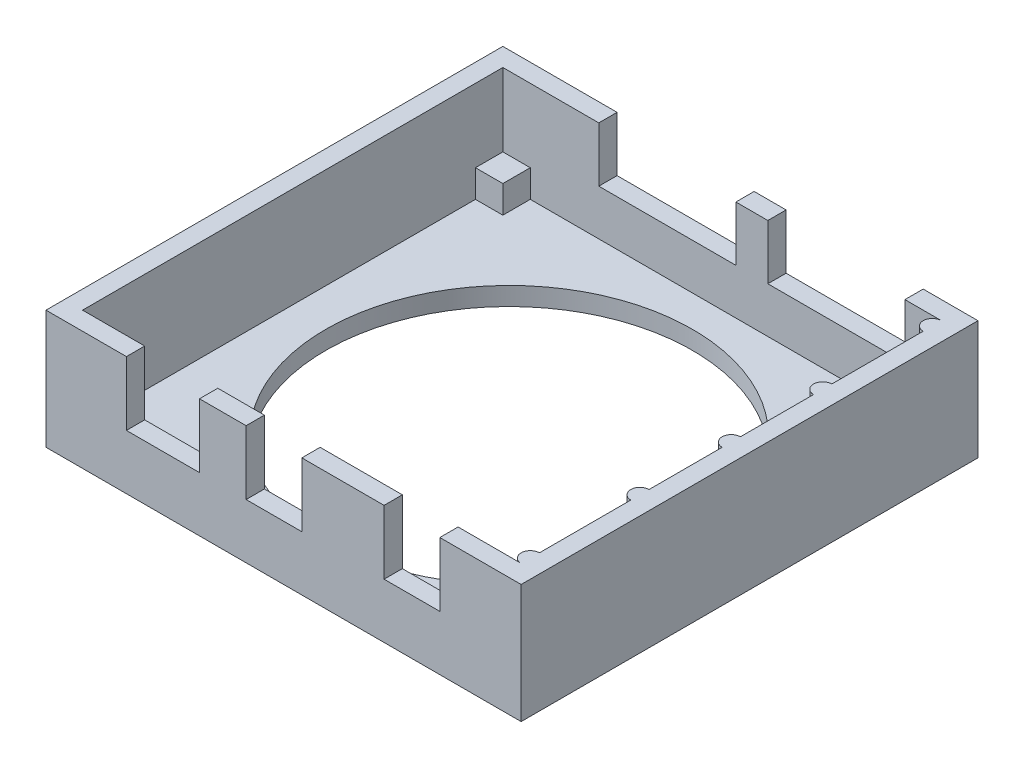
SolidWorks part; units mm, degrees
ref_plane "Front Plane" through (0, 0, 0) normal (0, 0, 1) x (1, 0, 0)
ref_plane "Top Plane" through (0, 0, 0) normal (0, 1, 0) x (1, 0, 0)
ref_plane "Right Plane" through (0, 0, 0) normal (1, 0, 0) x (0, 0, -1)
sketch "Sketch1" plane through (0, 0, 0) normal (0, 1, 0) x (1, 0, 0)
  line L1 (0, 50) -> (52, 50)
  line L2 (0, 50) -> (0, 0)
  line L3 (0, 0) -> (52, 0)
  line L4 (52, 50) -> (52, 0)
  dimension "D1" = 52
  dimension "D2" = 50
extrude "Boss-Extrude1" add sketch "Sketch1" along normal blind 13
sketch "Sketch2" plane through (0, 13, 0) normal (0, 1, 0) x (1, 0, 0)
  line L0 (0, 25) -> (52, 25) construction
  line L1 (2, 2) -> (50, 2)
  line L2 (2, 2) -> (2, 48)
  line L3 (2, 48) -> (50, 48)
  line L4 (50, 2) -> (50, 48)
  line L5 (0, 50) -> (0, 0) construction
  line L6 (52, 0) -> (52, 50) construction
  line L7 (26, 0) -> (26, 50) construction
  line L8 (0, 0) -> (52, 0) construction
  line L9 (52, 50) -> (0, 50) construction
  point P10 (2, 25)
  point P11 (26, 2)
  dimension "D1" = 46
  dimension "D2" = 48
extrude "Cut-Extrude1" cut sketch "Sketch2" against normal blind 11
sketch "Sketch3" plane through (0, 13, 0) normal (0, 1, 0) x (1, 0, 0)
  line L6 (50, 2) -> (50, 48) construction
  line L11 (2, 2) -> (50, 2) construction
  line L12 (43.1, 2) -> (37, 2)
  line L13 (43.1, 2) -> (43.1, 0)
  line L14 (43.1, 0) -> (37, 0)
  line L15 (37, 2) -> (37, 0)
  line L16 (0, 0) -> (52, 0) construction
  line L18 (28, 2) -> (21.9, 2)
  line L19 (28, 2) -> (28, 0)
  line L20 (28, 0) -> (21.9, 0)
  line L21 (21.9, 2) -> (21.9, 0)
  line L22 (16.8, 2) -> (8.8, 2)
  line L23 (16.8, 2) -> (16.8, 0)
  line L24 (16.8, 0) -> (8.8, 0)
  line L25 (8.8, 2) -> (8.8, 0)
  dimension "D5" = 6.9
  dimension "D6" = 6.1
  dimension "D7" = 9
  dimension "D8" = 6.1
  dimension "D9" = 5.1
  dimension "D10" = 8
extrude "Cut-Extrude2" cut sketch "Sketch3" against normal blind 7
sketch "Sketch4" plane through (0, 2, 0) normal (0, 1, 0) x (1, 0, 0)
  line L0 (2, 2) -> (50, 2) construction
  line L1 (2, 48) -> (5, 48)
  line L2 (2, 48) -> (2, 45)
  line L3 (2, 45) -> (5, 45)
  line L4 (5, 48) -> (5, 45)
  line L5 (50, 48) -> (47, 48)
  line L6 (50, 48) -> (50, 45)
  line L7 (50, 45) -> (47, 45)
  line L8 (47, 48) -> (47, 45)
  line L9 (2, 2) -> (5, 2)
  line L10 (2, 2) -> (2, 5)
  line L11 (2, 5) -> (5, 5)
  line L12 (5, 2) -> (5, 5)
  line L13 (2, 48) -> (2, 2) construction
  line L15 (50, 2) -> (47, 2)
  line L16 (50, 2) -> (50, 5)
  line L17 (50, 5) -> (47, 5)
  line L18 (47, 2) -> (47, 5)
  dimension "D1" = 3
  dimension "D2" = 3
  dimension "D3" = 3
  dimension "D4" = 3
extrude "Boss-Extrude2" add sketch "Sketch4" along normal blind 3
sketch "Sketch5" plane through (0, 2, 0) normal (0, 1, 0) x (1, 0, 0)
  line L1 (50, 5) -> (50, 45) construction
  circle A3 centre (50, 35) radius 1
  circle A4 centre (50, 25) radius 1
  circle A5 centre (50, 15) radius 1
  circle A9 centre (50, 47) radius 1
  circle A10 centre (50, 3) radius 1
  dimension "D6" = 12
  dimension "D7" = 12
extrude "Boss-Extrude3" add sketch "Sketch5" along normal up to surface (11 mm away) up to face at (25.9833, 13, -17)
sketch "Sketch13" plane through (0, 13, 0) normal (0, 1, 0) x (1, 0, 0)
  line L0 (52, 50) -> (0, 50) construction
  line L1 (46, 50) -> (31, 50)
  line L2 (46, 50) -> (46, 48)
  line L3 (46, 48) -> (31, 48)
  line L4 (31, 50) -> (31, 48)
  line L5 (50, 48) -> (2, 48) construction
  line L7 (27.5, 50) -> (12.5, 50)
  line L8 (27.5, 50) -> (27.5, 48)
  line L9 (27.5, 48) -> (12.5, 48)
  line L10 (12.5, 50) -> (12.5, 48)
  dimension "D1" = 4
  dimension "D2" = 15
  dimension "D3" = 3.5
  dimension "D4" = 15
extrude "Cut-Extrude4" cut sketch "Sketch13" against normal blind 6
sketch "Sketch12" plane through (0, 2, 0) normal (0, 1, 0) x (1, 0, 0)
  circle A0 centre (26.189, 24.4971) radius 20.0652
extrude "Cut-Extrude3" cut sketch "Sketch12" against normal blind 10
